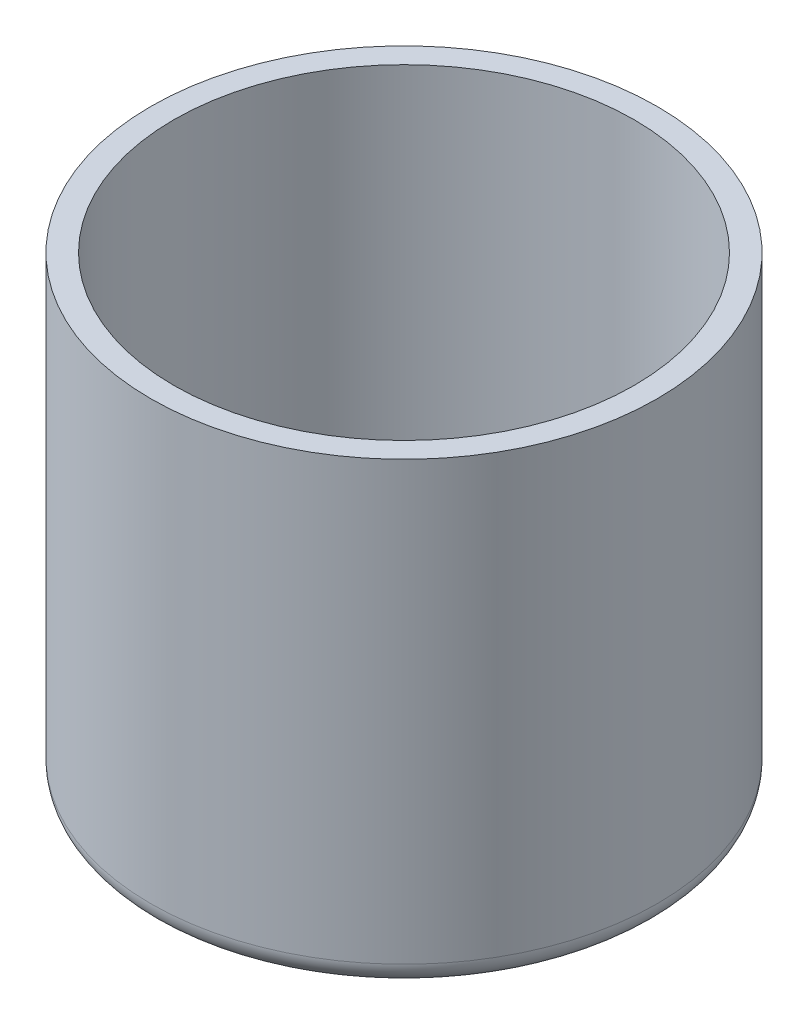
SolidWorks part; units mm, degrees
ref_plane "Front Plane" through (0, 0, 0) normal (0, 0, 1) x (1, 0, 0)
ref_plane "Top Plane" through (0, 0, 0) normal (0, 1, 0) x (1, 0, 0)
ref_plane "Right Plane" through (0, 0, 0) normal (1, 0, 0) x (0, 0, -1)
sketch "Sketch1" plane through (0, 0, 0) normal (0, 1, 0) x (1, 0, 0)
  circle A1 centre (0, 0) radius 11
  dimension "D2" = 22
extrude "Boss-Extrude1" add sketch "Sketch1" along normal blind 20
sketch "Sketch2" plane through (0, 20, 0) normal (0, 1, 0) x (1, 0, 0)
  circle A0 centre (0, 0) radius 10
  dimension "D1" = 20
extrude "Cut-Extrude1" cut sketch "Sketch2" against normal blind 18
fillet "Fillet1" radius 1 1 edges at (0, 0, 11)
sketch "Sketch3" plane through (0, 0, 0) normal (0, -1, 0) x (1, 0, 0)
  circle A0 centre (0, 0) radius 4
  dimension "D1" = 8
extrude "Cut-Extrude2" cut sketch "Sketch3" against normal up to next
